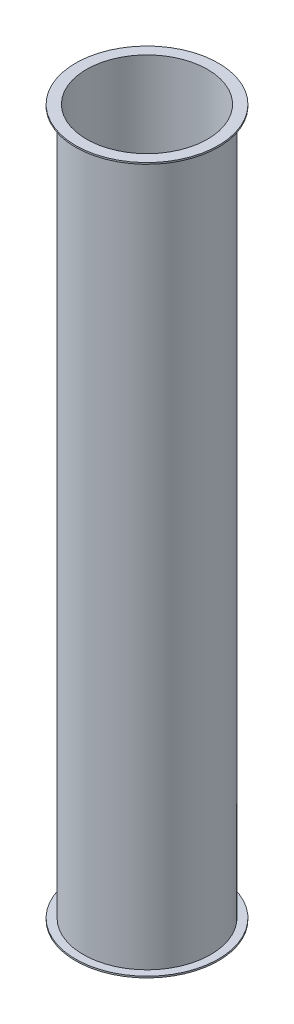
SolidWorks part; units mm, degrees
material "AISI 304"
ref_plane "Piano frontale" through (0, 0, 0) normal (0, 0, 1) x (1, 0, 0)
ref_plane "Piano superiore" through (0, 0, 0) normal (0, 1, 0) x (1, 0, 0)
ref_plane "Piano destro" through (0, 0, 0) normal (1, 0, 0) x (0, 0, -1)
sketch "Schizzo1" plane through (0, 0, 0) normal (0, 1, 0) x (1, 0, 0)
  circle A0 centre (0, 0) radius 39
extrude "Estrusione-Sottile1" add sketch "Schizzo1" along normal mid plane 455 thin
sketch "Schizzo2" plane through (0, 227.5, 0) normal (0, 1, 0) x (1, 0, 0)
  circle A0 centre (0, 0) radius 41 construction
  circle A1 centre (0, 0) radius 41
  circle A2 centre (0, 0) radius 46
extrude "Estrusione-Estrusione1" add sketch "Schizzo2" against normal blind 1
sketch "Schizzo3" plane through (0, -227.5, 0) normal (0, -1, 0) x (1, 0, 0)
  circle A0 centre (0, 0) radius 41 construction
  circle A1 centre (0, 0) radius 41
  circle A2 centre (0, 0) radius 46 construction
  circle A3 centre (0, 0) radius 46
extrude "Estrusione-Estrusione2" add sketch "Schizzo3" against normal blind 1
sketch "Schizzo4" plane through (0, -227.5, 0) normal (0, -1, 0) x (1, 0, 0)
  line L0 (24.5909, 0) -> (-24.5909, 0) construction
  line L1 (0, -22.0959) -> (0, 22.0959) construction
  point P5 (0, 0)
  point P9 (0, 0)
sketch "Schizzo5" plane through (0, 227.5, 0) normal (0, 1, 0) x (1, 0, 0)
  line L0 (24.5909, 0) -> (-24.5909, 0) construction
  line L1 (24.5909, 0) -> (-24.5909, 0) construction
  line L2 (0, 22.0959) -> (0, -22.0959) construction
  line L3 (0, 22.0959) -> (0, -22.0959) construction
